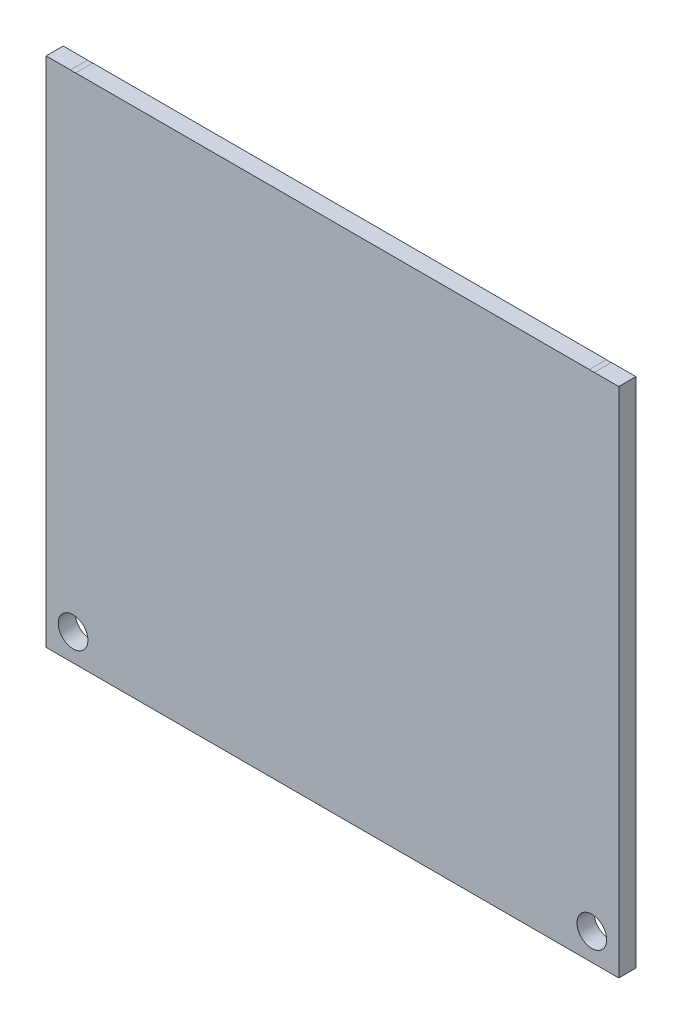
SolidWorks part; units mm, degrees
ref_plane "Front" through (0, 0, 0) normal (0, 0, 1) x (1, 0, 0)
ref_plane "Top" through (0, 0, 0) normal (0, 1, 0) x (1, 0, 0)
ref_plane "Right" through (0, 0, 0) normal (1, 0, 0) x (0, 0, -1)
sketch "Sketch1" plane through (0, 0, 0) normal (0, 0, 1) x (1, 0, 0)
  line L1 (-53.1, -47.5) -> (53.1, -47.5)
  line L2 (-53.1, -47.5) -> (-53.1, 47.5)
  line L3 (-53.1, 47.5) -> (53.1, 47.5)
  line L4 (53.1, -47.5) -> (53.1, 47.5)
  line L5 (-53.1, -47.5) -> (53.1, 47.5) construction
  line L6 (-53.1, 47.5) -> (53.1, -47.5) construction
  point P0 (0, 0)
  dimension "D1" = 95
  dimension "D2" = 106.2
extrude "Boss-Extrude1" add sketch "Sketch1" along normal blind 3.175
sketch "Sketch2" plane through (0, 0, 0) normal (0, 0, -1) x (-1, 0, 0)
  circle A0 centre (-48.1, 50.21) radius 2.75 construction
  circle A1 centre (-48.1, -42.5) radius 2.75 construction
  circle A2 centre (48.1, -42.5) radius 2.75 construction
  circle A3 centre (48.1, 50.21) radius 2.75 construction
  circle A4 centre (-48.1, 50.21) radius 2.75
  circle A5 centre (-48.1, -42.5) radius 2.75
  circle A6 centre (48.1, -42.5) radius 2.75
  circle A7 centre (48.1, 50.21) radius 2.75
extrude "Cut-Extrude1" cut sketch "Sketch2" against normal up to next
